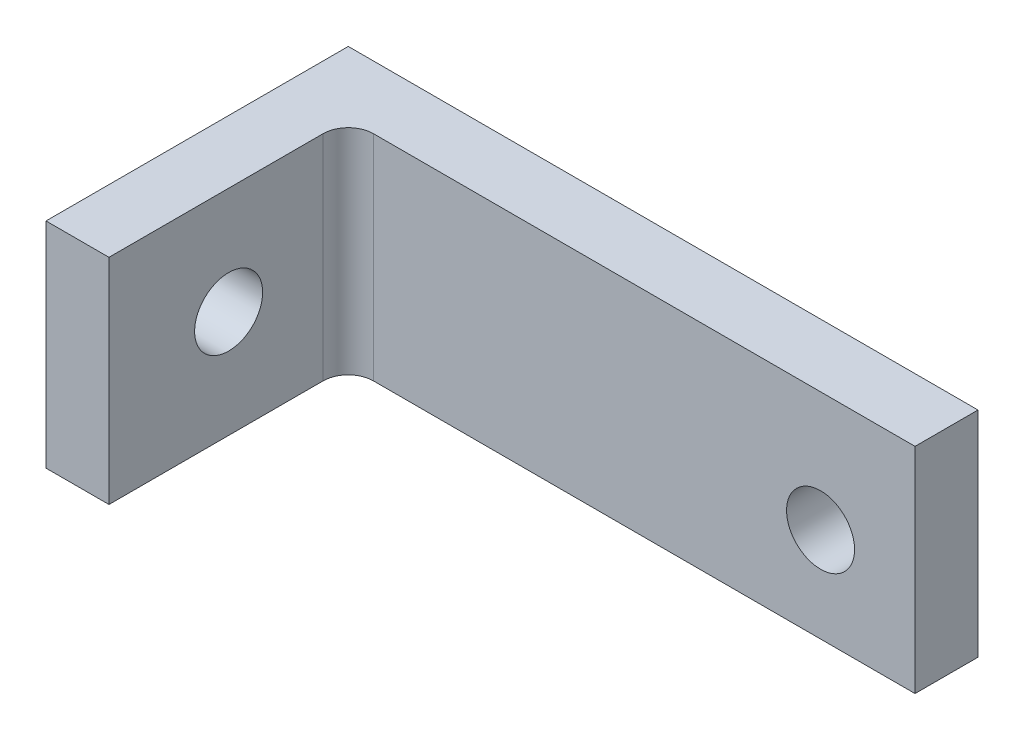
SolidWorks part; units mm, degrees
ref_plane "Front Plane" through (0, 0, 0) normal (0, 0, 1) x (1, 0, 0)
ref_plane "Top Plane" through (0, 0, 0) normal (0, 1, 0) x (1, 0, 0)
ref_plane "Right Plane" through (0, 0, 0) normal (1, 0, 0) x (0, 0, -1)
sketch "Sketch1" plane through (0, 0, 0) normal (0, 1, 0) x (1, 0, 0)
  line L0 (-25, 0) -> (25, 0)
  line L1 (-25, 0) -> (-25, -24)
  line L2 (-25, -24) -> (-20, -24)
  line L3 (25, 0) -> (25, -5)
  line L10 (-20, -24) -> (-20, -5)
  line L11 (-20, -5) -> (25, -5)
  dimension "D1" = 50
  dimension "D2" = 24
  dimension "D3" = 5
  dimension "D4" = 5
extrude "Boss-Extrude1" add sketch "Sketch1" along normal blind 17
sketch "Sketch2" plane through (-20, 0, 0) normal (1, 0, 0) x (0, 0, -1)
  line L0 (-14.5, 17) -> (-14.5, 0) construction
  line L1 (-24, 0) -> (-5, 0) construction
  line L2 (-24, 17) -> (-5, 17) construction
  circle A0 centre (-14.5, 8.5) radius 2.7
  dimension "D1" = 5.4
extrude "Cut-Extrude1" cut sketch "Sketch2" against normal through all
sketch "Sketch3" plane through (0, 0, 5) normal (0, 0, 1) x (1, 0, 0)
  line L0 (25, 17) -> (25, 0) construction
  line L1 (-20, 17) -> (25, 17) construction
  circle A0 centre (17.5, 7.5) radius 2.7
  dimension "D1" = 5.4
  dimension "D2" = 7.5
  dimension "D3" = 9.5
extrude "Cut-Extrude2" cut sketch "Sketch3" against normal through all
fillet "Fillet1" radius 2 1 edges at (-20, 8.5, 5)
